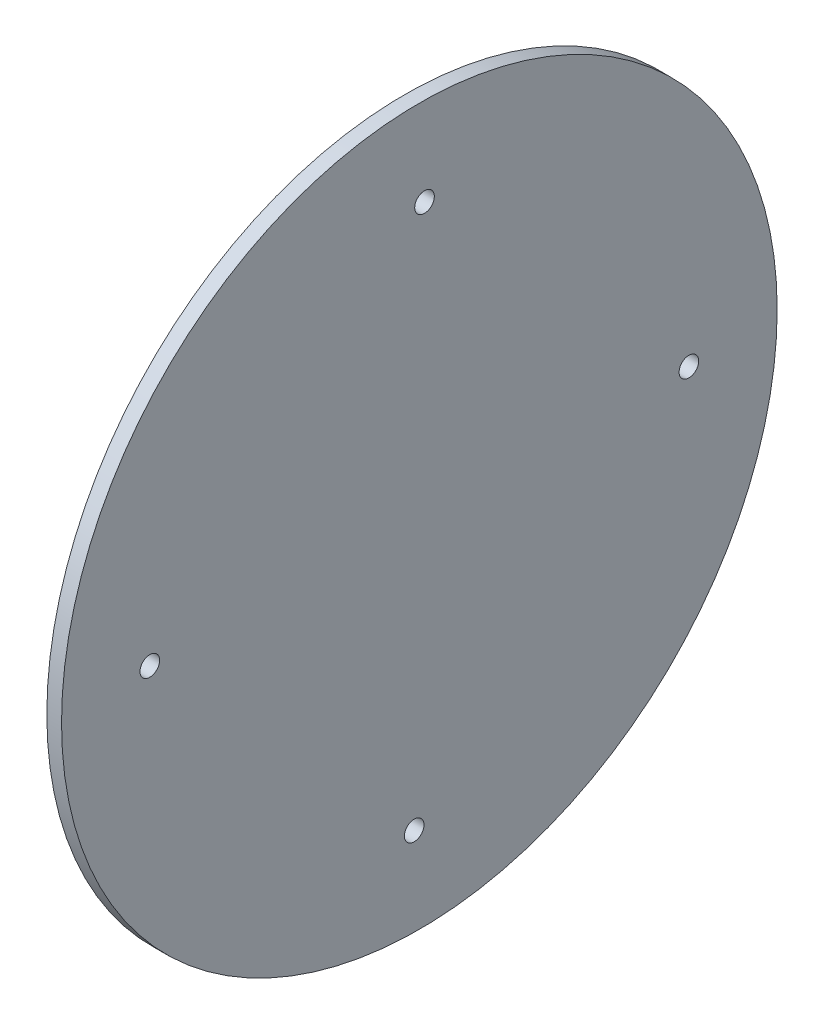
SolidWorks part; units mm, degrees
material "6061 Alloy"
ref_plane "Front Plane" through (0, 0, 0) normal (0, 0, 1) x (1, 0, 0)
ref_plane "Top Plane" through (0, 0, 0) normal (0, 1, 0) x (1, 0, 0)
ref_plane "Right Plane" through (0, 0, 0) normal (1, 0, 0) x (0, 0, -1)
sketch "Sketch1" plane through (0, 0, 0) normal (1, 0, 0) x (0, 0, -1)
  circle A0 centre (-28.5429, 18.9571) radius 36.5
  dimension "D1" = 73
extrude "Boss-Extrude1" add sketch "Sketch1" along normal blind 2
extrude "Cut-Extrude1" cut sketch "Sketch2" against normal through all
sketch "Sketch2" plane through (-11.5, 40.3264, 9.173) normal (-1, 0, 0) x (0, -0.9998, 0.0191)
  circle A0 centre (21.7363, 46.4571) radius 1
  circle A1 centre (21.7363, -8.5429) radius 1
  circle A2 centre (49.2363, 18.9571) radius 1
  circle A3 centre (-5.7637, 18.9571) radius 1
sketch "Sketch3" plane through (0, 0, 0) normal (1, 0, 0) x (0, 0, -1)
  circle A2 centre (-28.5429, 18.9571) radius 36.5
  circle A3 centre (-28.5429, 18.9571) radius 35
extrude "Cut-Extrude2" cut sketch "Sketch3" along normal blind 0.5
sketch "Sketch4" plane through (0.5, 0, 0) normal (-1, 0, 0) x (0, 0, 1)
  circle A0 centre (28.5429, 18.9571) radius 35
  circle A1 centre (28.5429, 18.9571) radius 35.5
  dimension "D1" = 0.5
extrude "Cut-Extrude3" cut sketch "Sketch4" against normal blind 0.25
